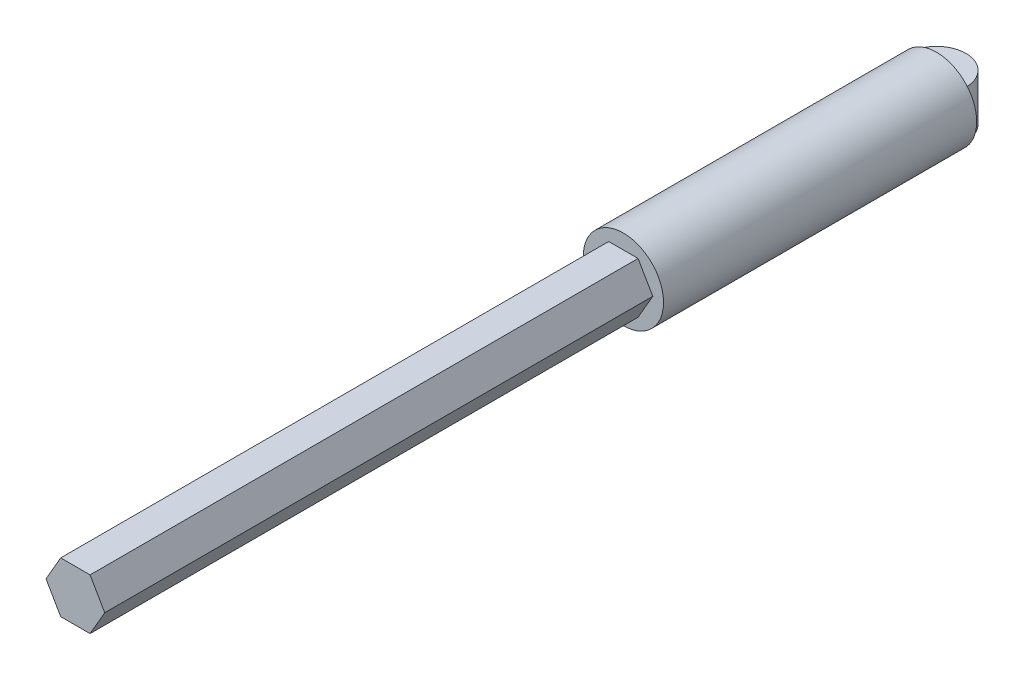
SolidWorks part; units mm, degrees
ref_plane "Front Plane" through (0, 0, 0) normal (0, 0, 1) x (1, 0, 0)
ref_plane "Top Plane" through (0, 0, 0) normal (0, 1, 0) x (1, 0, 0)
ref_plane "Right Plane" through (0, 0, 0) normal (1, 0, 0) x (0, 0, -1)
sketch "Sketch1" plane through (0, 0, 0) normal (0, 0, 1) x (1, 0, 0)
  circle A0 centre (0, 0) radius 1.025
  dimension "D1" = 2.05
extrude "Boss-Extrude1" add sketch "Sketch1" along normal blind 5
sketch "Sketch2" plane through (0, 0, 5) normal (0, 0, 1) x (1, 0, 0)
  line L0 (0, 0) -> (1.025, 0)
  line L2 (0.7506, 0) -> (0.3753, 0.65)
  line L3 (0.3753, 0.65) -> (-0.3753, 0.65)
  line L4 (-0.3753, 0.65) -> (-0.7506, 0)
  line L5 (-0.7506, 0) -> (-0.3753, -0.65)
  line L6 (-0.3753, -0.65) -> (0.3753, -0.65)
  line L7 (0.3753, -0.65) -> (0.7506, 0)
  circle A0 centre (0, 0) radius 1.025 construction
  circle A1 centre (0, 0) radius 0.65 construction
ref_plane "Plane3" through (0, 0, 0) normal (0, 1, 0) x (1, 0, 0)
sketch "Sketch3" plane through (0, 0, 0) normal (0, 1, 0) x (1, 0, 0)
  line L0 (-0.75, 0) -> (0.75, 0)
  arc A0 (0.75, 0) -> (-0.75, 0) centre (0, 0) ccw
  dimension "D1" = 1.5
extrude "Boss-Extrude5" add sketch "Sketch3" along normal blind 0.25 and the other way blind 0.2 contours A0 L0
sketch "Sketch5" plane through (0, 0.25, 0) normal (0, 1, 0) x (1, 0, 0)
  line L0 (-0.75, 0) -> (0.75, 0)
  circle A0 centre (0, 0) radius 0.75
  arc M1 (0.75, 0) -> (-0.75, 0) centre (0, 0) ccw
  line M2 (-0.75, 0) -> (0.75, 0)
  dimension "D1" = 1.5
extrude "Boss-Extrude6" add sketch "Sketch5" along normal blind 0.375 contours M2 M1
sketch "Sketch6" plane through (0, -0.2, 0) normal (0, -1, 0) x (1, 0, 0)
  line L0 (-0.75, 0) -> (0.75, 0)
  circle A0 centre (0, 0) radius 0.75
  arc M2 (-0.75, 0) -> (0.75, 0) centre (0, 0) ccw
  line M3 (0.75, 0) -> (-0.75, 0)
extrude "Boss-Extrude7" add sketch "Sketch6" along normal blind 0.375 contours M3 M2
extrude "Boss-Extrude9" add sketch "Sketch2" along normal blind 14
sketch "Sketch7" plane through (0, 0, 5) normal (0, 0, 1) x (1, 0, 0)
  circle A0 centre (0, 0) radius 1.025
extrude "Boss-Extrude10" add sketch "Sketch7" along normal blind 3
sketch "Sketch8" plane through (0, 0, 19) normal (0, 0, 1) x (1, 0, 0)
  line L1 (0.7506, 0) -> (0.3753, 0.65)
  line L2 (0.3753, 0.65) -> (-0.3753, 0.65)
  line L3 (-0.3753, 0.65) -> (-0.7506, 0)
  line L4 (-0.7506, 0) -> (-0.3753, -0.65)
  line L5 (-0.3753, -0.65) -> (0.3753, -0.65)
  line L6 (0.3753, -0.65) -> (0.7506, 0)
  circle A0 centre (0, 0) radius 0.65 construction
extrude "Boss-Extrude11" add sketch "Sketch8" along normal blind 3
